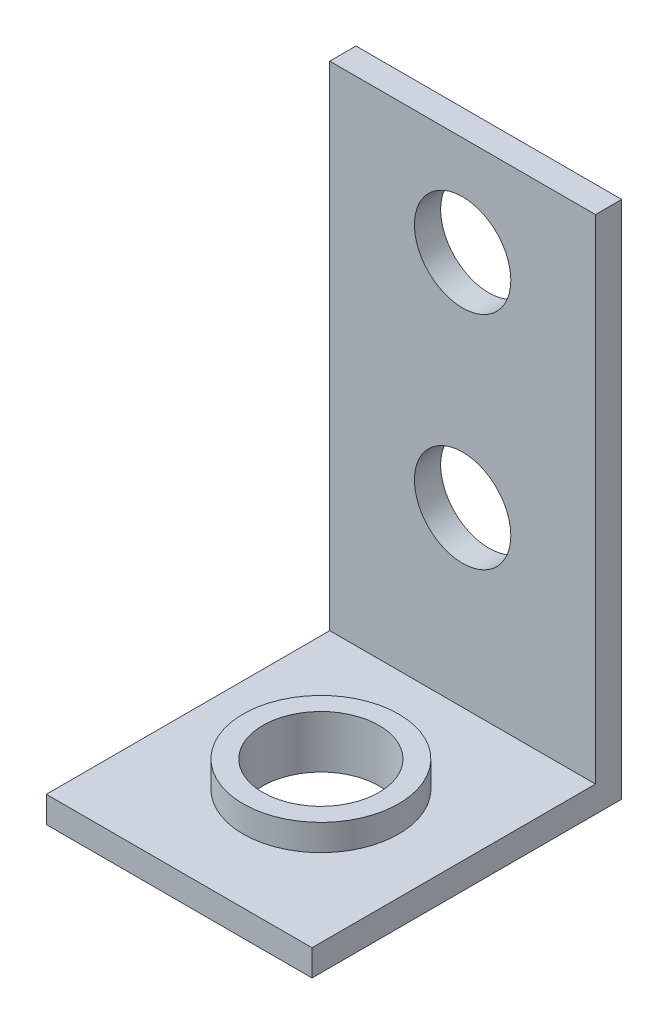
SolidWorks part; units mm, degrees
ref_plane "Front Plane" through (0, 0, 0) normal (0, 0, 1) x (1, 0, 0)
ref_plane "Top Plane" through (0, 0, 0) normal (0, 1, 0) x (1, 0, 0)
ref_plane "Right Plane" through (0, 0, 0) normal (1, 0, 0) x (0, 0, -1)
sketch "Sketch1" plane through (0, 0, 0) normal (0, 1, 0) x (1, 0, 0)
  line L1 (0, 0) -> (9.525, 0)
  line L2 (0, 0) -> (0, 11.0998)
  line L3 (0, 11.0998) -> (9.525, 11.0998)
  line L4 (9.525, 0) -> (9.525, 11.0998)
  dimension "D1" = 11.0998
  dimension "D2" = 9.525
extrude "Boss-Extrude1" add sketch "Sketch1" along normal blind 0.9398
sketch "Sketch2" plane through (0, 0.9398, 0) normal (0, 1, 0) x (1, 0, 0)
  line L0 (9.525, 0) -> (9.525, 11.0998) construction
  line L1 (0, 11.0998) -> (9.525, 11.0998)
  line L2 (0, 11.0998) -> (0, 10.16)
  line L3 (0, 10.16) -> (9.525, 10.16)
  line L4 (9.525, 11.0998) -> (9.525, 10.16)
  dimension "D1" = 0.9398
extrude "Boss-Extrude2" add sketch "Sketch2" along normal blind 17.6784
sketch "Sketch3" plane through (0, 0, -10.16) normal (0, 0, 1) x (1, 0, 0)
  line L0 (4.7625, 18.6182) -> (4.7625, 0.9398)
  line L1 (0, 18.6182) -> (9.525, 18.6182) construction
  line L2 (0, 0.9398) -> (9.525, 0.9398) construction
  circle A0 centre (4.7625, 15.0622) radius 1.7272
  circle A1 centre (4.7625, 7.1374) radius 1.7272
  dimension "D1" = 3.4544
  dimension "D2" = 3.4544
  dimension "D3" = 6.1976
  dimension "D4" = 7.9248
extrude "Cut-Extrude1" cut sketch "Sketch3" against normal through all contours L0 A0 | L0 A0 | L0 A1 | L0 A1
sketch "Sketch4" plane through (0, 0.9398, 0) normal (0, 1, 0) x (1, 0, 0)
  line L0 (4.7625, 10.16) -> (4.7625, 0)
  line L1 (0, 10.16) -> (9.525, 10.16) construction
  line L2 (0, 0) -> (9.525, 0) construction
  line L3 (0, 5.08) -> (9.525, 5.08)
  line L4 (0, 10.16) -> (0, 0) construction
  line L5 (9.525, 0) -> (9.525, 10.16) construction
  circle A0 centre (4.7625, 5.08) radius 2.0828
  dimension "D1" = 4.1656
extrude "Cut-Extrude2" cut sketch "Sketch4" against normal through all contours L0 A0 L3 | L3 A0 L0 | L0 A0 L3 | L3 A0 L0
sketch "Sketch7" plane through (0, 0.9398, 0) normal (0, 1, 0) x (1, 0, 0)
  circle A0 centre (4.7625, 5.08) radius 2.0828
  circle A1 centre (4.7625, 5.08) radius 2.7877
  dimension "D1" = 4.1656
  dimension "D2" = 0.7048
extrude "Boss-Extrude3" add sketch "Sketch7" along normal blind 0.9398
